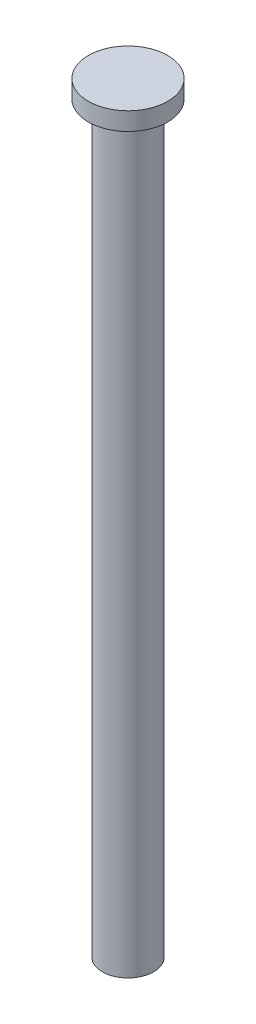
SolidWorks part; units mm, degrees
ref_plane "Front Plane" through (0, 0, 0) normal (0, 0, 1) x (1, 0, 0)
ref_plane "Top Plane" through (0, 0, 0) normal (0, 1, 0) x (1, 0, 0)
ref_plane "Right Plane" through (0, 0, 0) normal (1, 0, 0) x (0, 0, -1)
sketch "Sketch1" plane through (0, 0, 0) normal (0, 0, 1) x (1, 0, 0)
  line L0 (0, 0) -> (0, 297) construction
  line L1 (10, 0) -> (8.47, 0)
  line L2 (8.47, 0) -> (8.47, 290)
  line L3 (10, 0) -> (10, 290)
  line L4 (0, 297) -> (15.5, 297)
  line L5 (15.5, 297) -> (15.5, 290)
  line L6 (15.5, 290) -> (10, 290)
  line L7 (8.47, 290) -> (0, 290)
  line L8 (0, 297) -> (0, 290)
  dimension "D1" = 297
  dimension "D2" = 1.53
  dimension "D3" = 20
  dimension "D4" = 7
  dimension "D5" = 31
revolve "Revolve1" add sketch "Sketch1" angle 360 about L0
